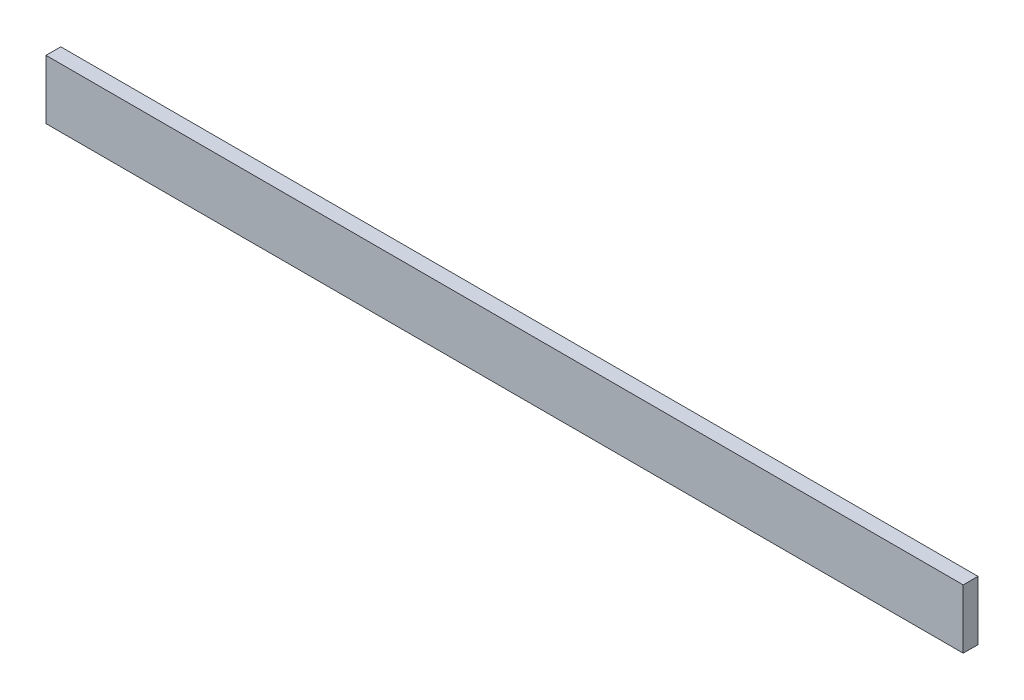
SolidWorks part; units mm, degrees
material "Plastique personnalisé"
ref_plane "Plan de face" through (0, 0, 0) normal (0, 0, 1) x (1, 0, 0)
ref_plane "Plan de dessus" through (0, 0, 0) normal (0, 1, 0) x (1, 0, 0)
ref_plane "Plan de droite" through (0, 0, 0) normal (1, 0, 0) x (0, 0, -1)
sketch "Esquisse1" plane through (0, 0, 0) normal (0, 0, 1) x (1, 0, 0)
  line L1 (0, 0) -> (310, 0)
  line L2 (0, 0) -> (0, 20)
  line L3 (0, 20) -> (310, 20)
  line L4 (310, 0) -> (310, 20)
  dimension "D1" = 310
  dimension "D2" = 20
extrude "Boss.-Extru.1" add sketch "Esquisse1" along normal blind 5
